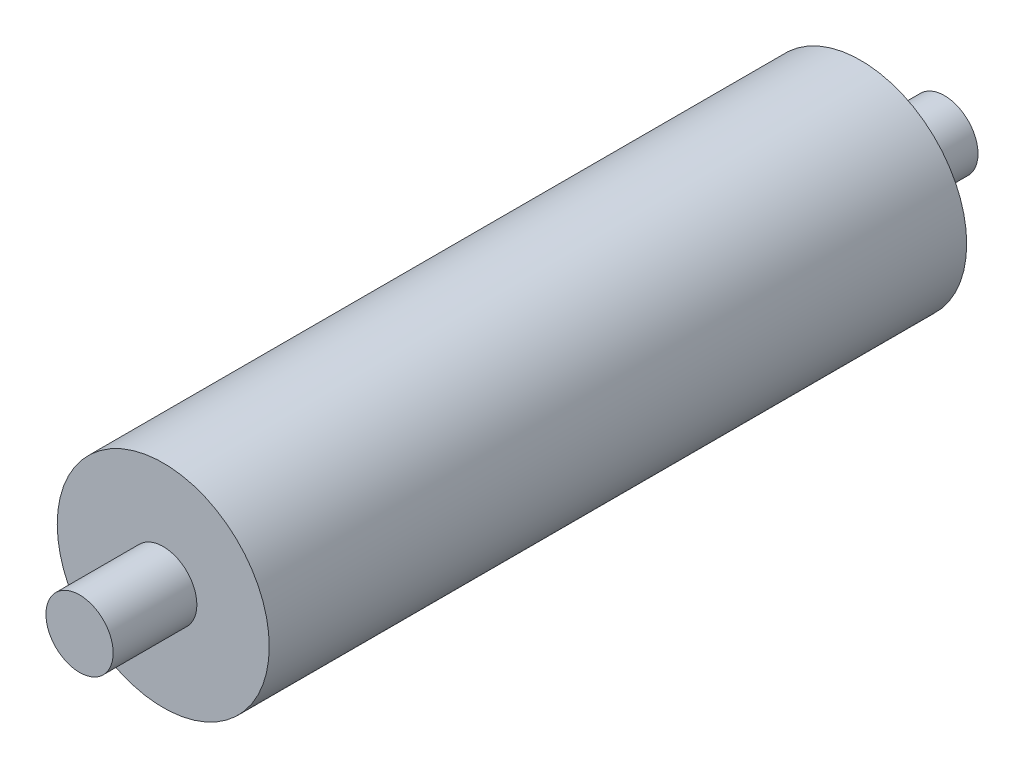
SolidWorks part; units mm, degrees
ref_plane "Front Plane" through (0, 0, 0) normal (0, 0, 1) x (1, 0, 0)
ref_plane "Top Plane" through (0, 0, 0) normal (0, 1, 0) x (1, 0, 0)
ref_plane "Right Plane" through (0, 0, 0) normal (1, 0, 0) x (0, 0, -1)
sketch "Sketch1" plane through (0, 0, 0) normal (0, 0, 1) x (1, 0, 0)
  circle A0 centre (0, 0) radius 14
  circle A1 centre (0, 0) radius 19
  dimension "D1" = 28
  dimension "D2" = 38
extrude "Boss-Extrude1" add sketch "Sketch1" against normal blind 125
ref_plane "Plane1" through (0, 0, -7.5) normal (0, 0, 1) x (1, 0, 0)
sketch "Sketch2" plane through (0, 0, -7.5) normal (0, 0, 1) x (1, 0, 0)
  circle A0 centre (0, 0) radius 14
  circle A1 centre (0, 0) radius 14 construction
extrude "Boss-Extrude2" add sketch "Sketch2" along normal up to surface (7.5 mm away) up to face at (14, 0, 0)
sketch "Sketch4" plane through (0, 0, -7.5) normal (0, 0, 1) x (1, 0, 0)
  circle A0 centre (0, 0) radius 6.025
  circle A1 centre (0, 0) radius 14 construction
  dimension "D1" = 12.05
extrude "Cut-Extrude1" cut sketch "Sketch4" against normal through all both and the other way through all
ref_plane "Plane2" through (0, 0, -117.5) normal (0, 0, -1) x (-1, 0, 0)
sketch "Sketch5" plane through (0, 0, -117.5) normal (0, 0, -1) x (-1, 0, 0)
  circle A0 centre (0, 0) radius 14
  circle A1 centre (0, 0) radius 14 construction
extrude "Boss-Extrude3" add sketch "Sketch5" along normal blind 7.5
sketch "Sketch7" plane through (0, 0, 0) normal (0, 0, 1) x (1, 0, 0)
  circle A0 centre (0, 0) radius 6.025
  circle A1 centre (0, 0) radius 6.025 construction
extrude "Boss-Extrude4" add sketch "Sketch7" along normal blind 15 and the other way blind 140
ref_plane "Plane3" through (0, 0, -62.5) normal (0, 0, 1) x (1, 0, 0)
sketch "Sketch8" plane through (0, 0, -62.5) normal (0, 0, 1) x (1, 0, 0)
  circle A0 centre (0, 0) radius 15
  dimension "D1" = 30
extrude "Boss-Extrude5" add sketch "Sketch8" along normal blind 5 and the other way blind 5
pattern_linear "LPattern2" count 2 spacing 30 along (0, 0, -1) of "Boss-Extrude5"
pattern_linear "LPattern3" count 2 spacing 30 along (0, 0, 1) of "LPattern2"
